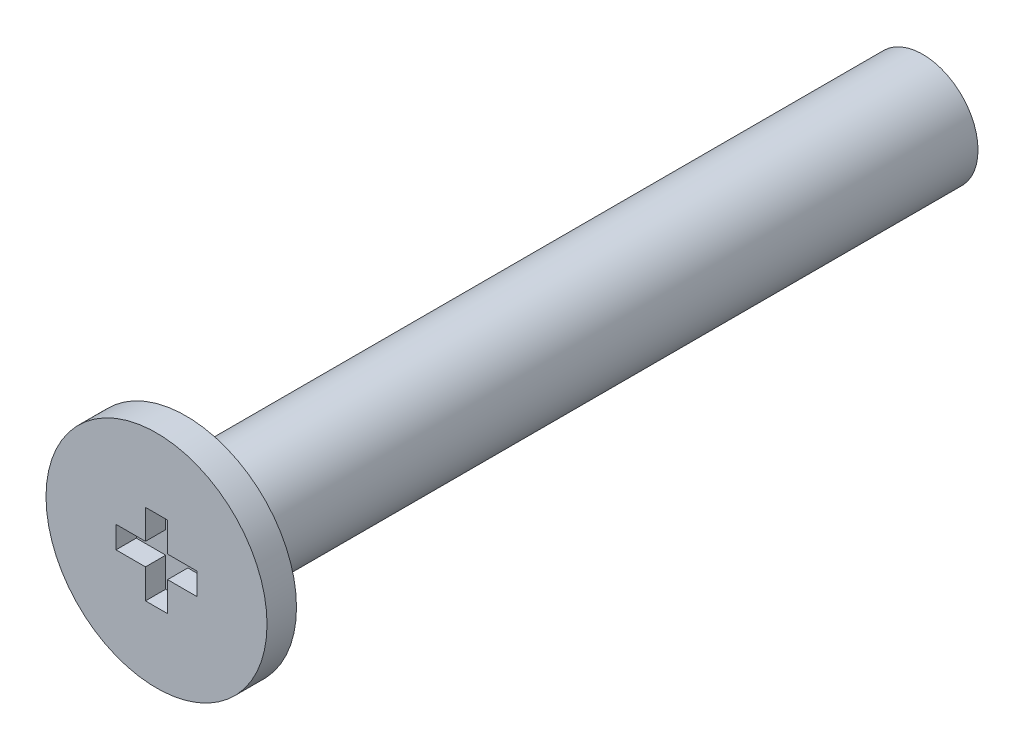
SolidWorks part; units mm, degrees
ref_plane "前视基准面" through (0, 0, 0) normal (0, 0, 1) x (1, 0, 0)
ref_plane "上视基准面" through (0, 0, 0) normal (0, 1, 0) x (1, 0, 0)
ref_plane "右视基准面" through (0, 0, 0) normal (1, 0, 0) x (0, 0, -1)
other "Configuration Table"
sketch "草图1" plane through (0, 0, 0) normal (0, 0, 1) x (1, 0, 0)
  circle A0 centre (0, 0) radius 1.5
extrude "标准杆径_头下长度" add sketch "草图1" against normal blind 20
sketch "草图2" plane through (0, 0, 0) normal (0, 0, 1) x (1, 0, 0)
  circle A0 centre (0, 0) radius 2.75
sketch "草图4" plane through (0, 0, 0) normal (0, 1, 0) x (1, 0, 0)
  line L0 (0, 0) -> (3.45, 0)
  line L1 (3.45, 0) -> (3.45, -0.3426)
  line L2 (0, -1.9) -> (0, 0)
  line L3 (0, 2) -> (0, -3.9) construction
  arc A0 (3.45, -0.3426) -> (0, -1.9) centre (0, 2.7) cw
sketch "草图5" plane through (0, 0, 0) normal (0, 0, 1) x (1, 0, 0)
  line L0 (-0.3, -1.45) -> (0.3, -1.45)
  line L1 (0.3, -1.45) -> (0.3, -0.3)
  line L2 (0.3, -0.3) -> (1.45, -0.3)
  line L3 (1.45, -0.3) -> (1.45, 0.3)
  line L4 (1.45, 0.3) -> (0.3, 0.3)
  line L5 (0.3, 0.3) -> (0.3, 1.45)
  line L6 (0.3, 1.45) -> (-0.3, 1.45)
  line L7 (-0.3, 1.45) -> (-0.3, 0.3)
  line L8 (-0.3, 0.3) -> (-1.45, 0.3)
  line L9 (-1.45, 0.3) -> (-1.45, -0.3)
  line L10 (-1.45, -0.3) -> (-0.3, -0.3)
  line L11 (-0.3, -0.3) -> (-0.3, -1.45)
sketch "草图6" plane through (0, 0, 0) normal (0, 1, 0) x (1, 0, 0)
  line L0 (0, 0) -> (3, 0)
  line L1 (3, 0) -> (3, -0.8)
  line L2 (3, -0.8) -> (0, -0.8)
  line L3 (0, -0.8) -> (0, 0)
  line L4 (0, 2) -> (0, -2.8) construction
revolve "已确认_十字槽超薄头" add sketch "草图6" angle 360 about L4
sketch "草图7" plane through (0, 0, 0) normal (0, 0, 1) x (1, 0, 0)
  line L0 (-0.3, -1.1) -> (0.3, -1.1)
  line L1 (0.3, -1.1) -> (0.3, -0.3)
  line L2 (0.3, -0.3) -> (1.1, -0.3)
  line L3 (1.1, -0.3) -> (1.1, 0.3)
  line L4 (1.1, 0.3) -> (0.3, 0.3)
  line L5 (0.3, 0.3) -> (0.3, 1.1)
  line L6 (0.3, 1.1) -> (-0.3, 1.1)
  line L7 (-0.3, 1.1) -> (-0.3, 0.3)
  line L8 (-0.3, 0.3) -> (-1.1, 0.3)
  line L9 (-1.1, 0.3) -> (-1.1, -0.3)
  line L10 (-1.1, -0.3) -> (-0.3, -0.3)
  line L11 (-0.3, -0.3) -> (-0.3, -1.1)
extrude "十字槽_PH1_简化" cut sketch "草图7" against normal blind 0.56 from offset 0.81
